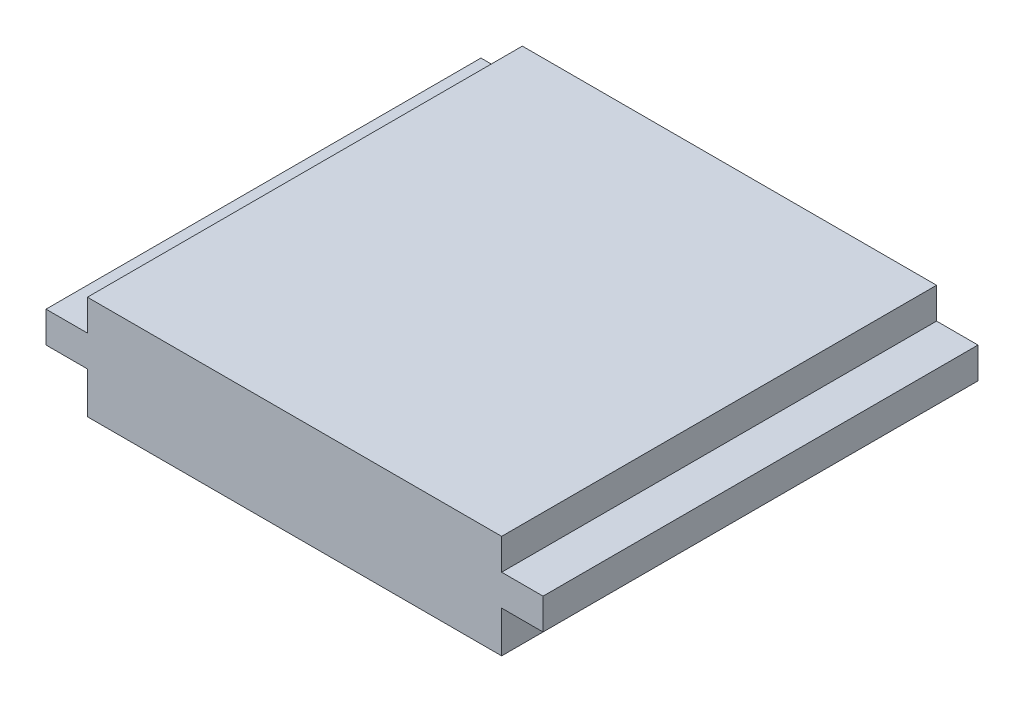
SolidWorks part; units mm, degrees
material "PVC Rigid"
ref_plane "Front Plane" through (0, 0, 0) normal (0, 0, 1) x (1, 0, 0)
ref_plane "Top Plane" through (0, 0, 0) normal (0, 1, 0) x (1, 0, 0)
ref_plane "Right Plane" through (0, 0, 0) normal (1, 0, 0) x (0, 0, -1)
sketch "Sketch1" plane through (0, 0, 0) normal (0, 0, 1) x (1, 0, 0)
  line L0 (0, 0) -> (20, 0)
  line L1 (20, 0) -> (20, 2)
  line L2 (20, 2) -> (22, 2)
  line L3 (22, 2) -> (22, 3.5)
  line L4 (22, 3.5) -> (20, 3.5)
  line L5 (20, 3.5) -> (20, 5)
  line L6 (20, 5) -> (0, 5)
  line L7 (0, 5) -> (0, 3.5)
  line L8 (0, 3.5) -> (-2, 3.5)
  line L9 (-2, 3.5) -> (-2, 2)
  line L10 (-2, 2) -> (0, 2)
  line L11 (0, 2) -> (0, 0)
  point P10 (-1, 2)
  dimension "D1" = 20
  dimension "D2" = 2
  dimension "D3" = 1.5
  dimension "D4" = 5
  dimension "D5" = 2
  dimension "D6" = 2
  dimension "D7" = 1.5
extrude "Boss-Extrude1" add sketch "Sketch1" along normal blind 21
